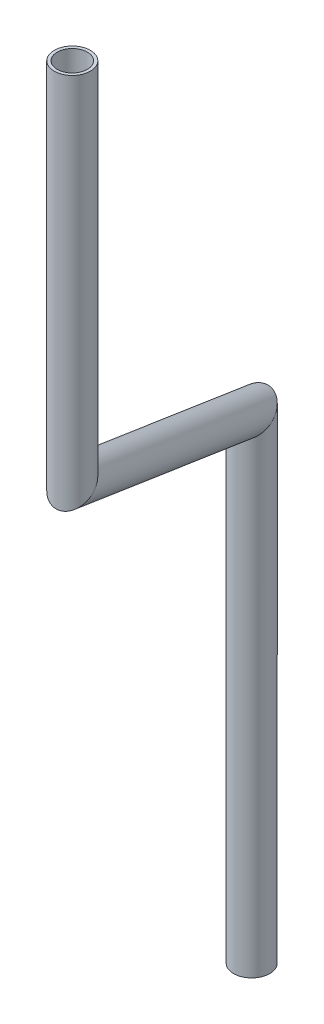
SolidWorks part; units mm, degrees
ref_plane "Front Plane" through (0, 0, 0) normal (0, 0, 1) x (1, 0, 0)
ref_plane "Top Plane" through (0, 0, 0) normal (0, 1, 0) x (1, 0, 0)
ref_plane "Right Plane" through (0, 0, 0) normal (1, 0, 0) x (0, 0, -1)
sketch3d "3DSketch1"
  line L0 (-803.8721, -70.1675, 358.3505) -> (-803.8721, -198.6889, 358.3505)
  line L1 (-803.8721, -198.6889, 358.3505) -> (-824.9646, -229.4117, 274.1878)
  line L2 (-824.9646, -229.4117, 274.1878) -> (-824.9646, -397.5265, 274.1878)
  line L7 (-803.8721, -198.6889, 358.3505) -> (-803.8721, -107.093, 358.3505) construction
  circle A4 centre (-824.9646, -397.5265, 274.1878) radius 5.2832 construction
  circle A7 centre (-803.8721, -70.1675, 358.3505) radius 8.0124 construction
  point P1 (-824.9646, -229.4117, 274.1878)
  point P2 (-803.8721, -198.6889, 358.3505)
  point P17 (-828.8164, 23.7998, 270.7645)
  point P29 (-824.9646, -402.8097, 274.1878)
  point P31 (-803.8721, -78.1799, 358.3505)
other "Pipe 0.5 SCH 40(1)"
ref_plane "Plane1" through (-803.8721, -70.1675, 358.3505) normal (0, -1, 0) x (1, 0, 0)
sketch "Sketch1" plane through (-803.8721, -70.1675, 358.3505) normal (0, -1, 0) x (1, 0, 0)
  circle A0 centre (0, 0) radius 5.2832
  circle A1 centre (0, 0) radius 6.35
  point P5 (0, 0)
  dimension "In_dia" = 10.5664
  dimension "Out_dia" = 12.7
